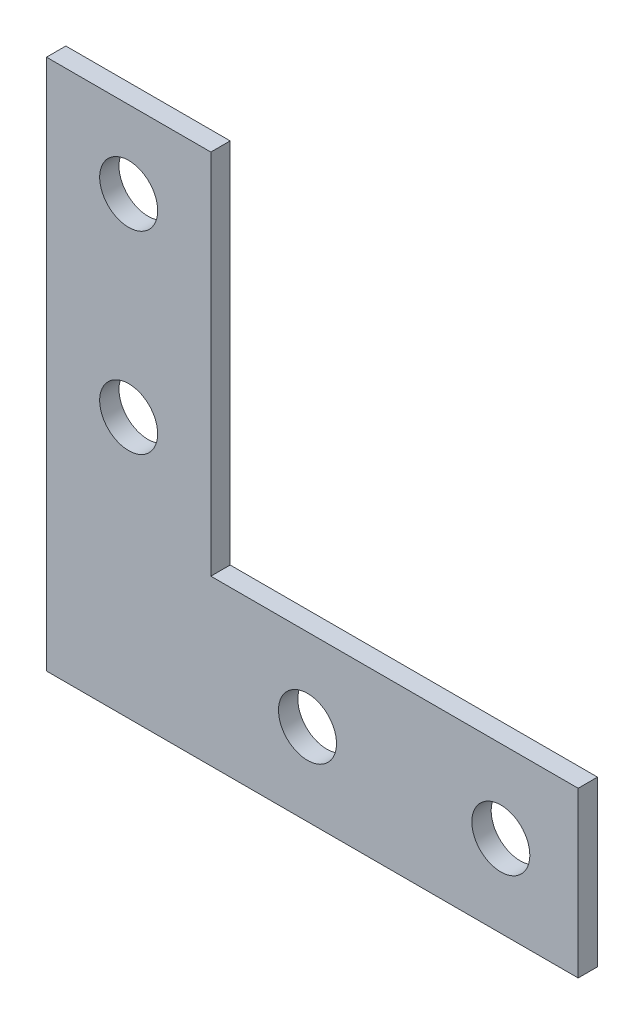
SolidWorks part; units mm, degrees
ref_plane "前视基准面" through (0, 0, 0) normal (0, 0, 1) x (1, 0, 0)
ref_plane "上视基准面" through (0, 0, 0) normal (0, 1, 0) x (1, 0, 0)
ref_plane "右视基准面" through (0, 0, 0) normal (1, 0, 0) x (0, 0, -1)
sketch "草图1" plane through (0, 0, 0) normal (0, 0, 1) x (1, 0, 0)
  line L0 (-8.5, -27.5) -> (28.5105, 9.5105) construction
  line L1 (-8.5, -27.5) -> (8.5, -27.5)
  line L2 (-8.5, -27.5) -> (-8.5, 27.5)
  line L3 (-8.5, 27.5) -> (8.5, 27.5)
  line L4 (8.5, -27.5) -> (8.5, 27.5)
  line L5 (-8.5, -27.5) -> (8.5, 27.5) construction
  line L6 (-8.5, 27.5) -> (8.5, -27.5) construction
  point P0 (0, 0)
  dimension "D1" = 17
  dimension "D2" = 55
  dimension "D3" = 45
extrude "凸台-拉伸1" add sketch "草图1" along normal blind 2
ref_plane "基准面1" through (9.5, -9.5, 0) normal (0.7071, -0.7071, 0) x (-0.7071, -0.7071, 0)
mirror "镜向1" about plane through (9.5, -9.5, 0) normal (0.7071, -0.7071, 0) of "凸台-拉伸1"
sketch "草图2" plane through (0, 0, 2) normal (0, 0, 1) x (1, 0, 0)
  line L0 (8.5, 27.5) -> (-8.5, 27.5) construction
  circle A0 centre (0, 19.5) radius 3
  circle A1 centre (0, -0.5) radius 3
  dimension "D1" = 8
  dimension "D2" = 6
  dimension "D3" = 20
extrude "切除-拉伸1" cut sketch "草图2" against normal blind 10
ref_plane "基准面2" through (9.5, -9.5, 0) normal (0.7071, -0.7071, 0) x (0, 0, -1)
mirror "镜向2" about plane through (9.5, -9.5, 0) normal (0.7071, -0.7071, 0) of "切除-拉伸1"
